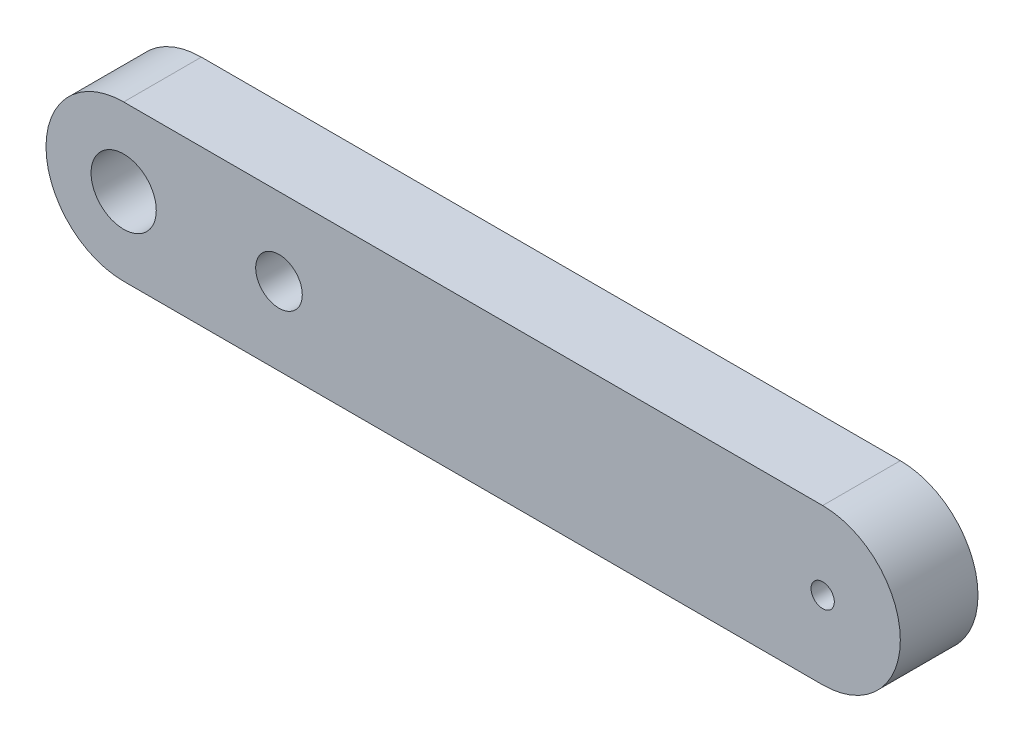
SolidWorks part; units mm, degrees
ref_plane "Front Plane" through (0, 0, 0) normal (0, 0, 1) x (1, 0, 0)
ref_plane "Top Plane" through (0, 0, 0) normal (0, 1, 0) x (1, 0, 0)
ref_plane "Right Plane" through (0, 0, 0) normal (1, 0, 0) x (0, 0, -1)
sketch "Sketch1" plane through (0, 0, 0) normal (0, 0, 1) x (1, 0, 0)
  line L0 (-81.5176, 36.7885) -> (-36.5176, 36.7885)
  line L2 (-36.5176, 26.7885) -> (-81.5176, 26.7885)
  arc A0 (-81.5176, 36.7885) -> (-81.5176, 26.7885) centre (-81.5176, 31.7885) ccw
  arc A1 (-36.5176, 26.7885) -> (-36.5176, 36.7885) centre (-36.5176, 31.7885) ccw
  circle A2 centre (-81.5176, 31.7885) radius 1.5
  circle A3 centre (-36.5176, 31.7885) radius 0.75
extrude "Boss-Extrude1" add sketch "Sketch1" along normal blind 4
sketch "Sketch2" plane through (0, 0, 4) normal (0, 0, 1) x (1, 0, 0)
  circle A0 centre (-71.5176, 31.7885) radius 1.25
extrude "Cut-Extrude1" cut sketch "Sketch2" against normal blind 4
sketch "Sketch3" plane through (0, 0, 4) normal (0, 0, 1) x (1, 0, 0)
  circle A0 centre (-71.5176, 31.7885) radius 1.5
extrude "Cut-Extrude2" cut sketch "Sketch3" against normal blind 10
sketch "Sketch4" plane through (0, 0, 4) normal (0, 0, 1) x (1, 0, 0)
  line L0 (-81.5176, 36.7885) -> (-36.5176, 36.7885)
  line L1 (-81.5176, 26.7885) -> (-36.5176, 26.7885)
  circle A0 centre (-81.5176, 31.7885) radius 1.5
  circle A1 centre (-71.5176, 31.7885) radius 1.5
  circle A2 centre (-36.5176, 31.7885) radius 0.75
  arc A3 (-81.5176, 36.7885) -> (-81.5176, 26.7885) centre (-81.5176, 31.7885) ccw
  arc A4 (-36.5176, 26.7885) -> (-36.5176, 36.7885) centre (-36.5176, 31.7885) ccw
extrude "Boss-Extrude2" add sketch "Sketch4" along normal blind 1
sketch "Sketch5" plane through (0, 0, 5) normal (0, 0, 1) x (1, 0, 0)
  circle A0 centre (-81.5176, 31.7885) radius 2.1
extrude "Cut-Extrude3" cut sketch "Sketch5" against normal blind 10
